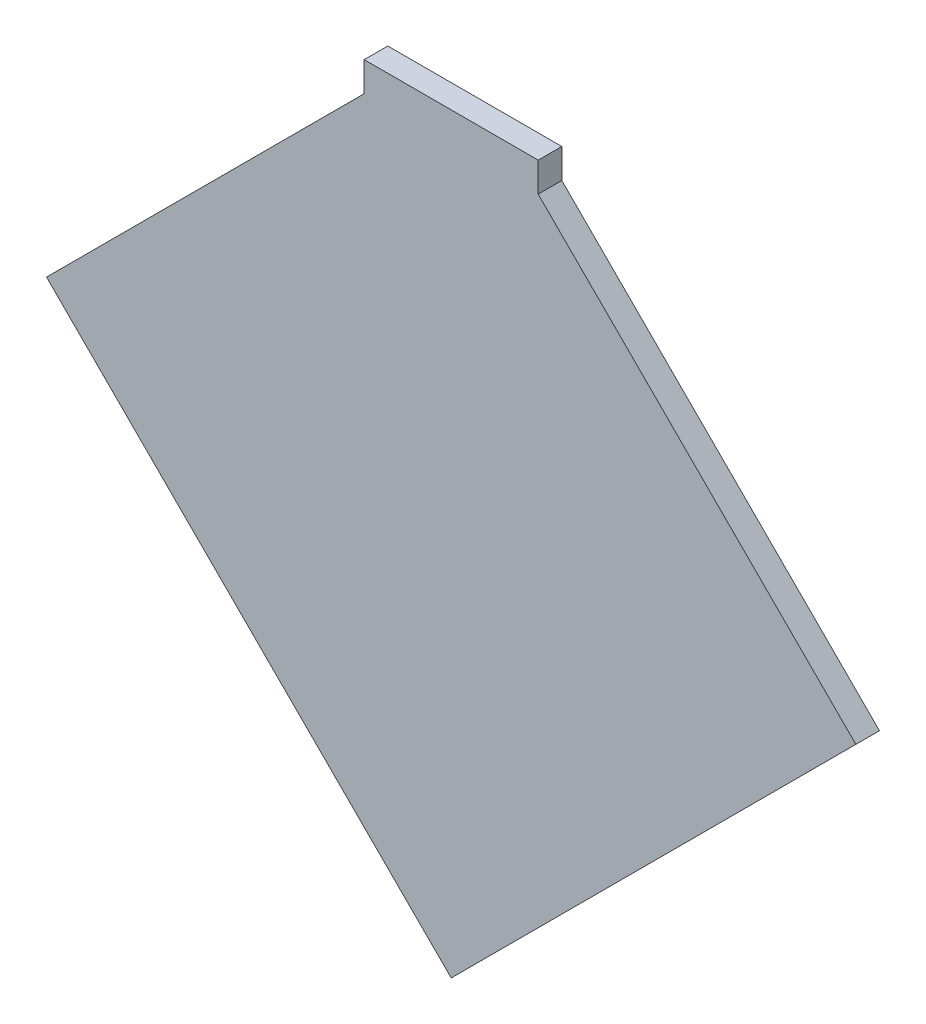
SolidWorks part; units mm, degrees
ref_plane "Front Plane" through (0, 0, 0) normal (0, 0, 1) x (1, 0, 0)
ref_plane "Top Plane" through (0, 0, 0) normal (0, 1, 0) x (1, 0, 0)
ref_plane "Right Plane" through (0, 0, 0) normal (1, 0, 0) x (0, 0, -1)
sketch "Sketch1" plane through (0, 0, 0) normal (0, 0, 1) x (1, 0, 0)
  line L0 (-4.6243, 15.9525) -> (-20.5768, 0)
  line L1 (-20.5768, 0) -> (0, -20.5768)
  line L2 (0, -20.5768) -> (20.5768, 0)
  line L3 (20.5768, 0) -> (4.6243, 15.9525)
  line L4 (4.6243, 15.9525) -> (4.4828, 15.9525)
  line L5 (4.4828, 15.9525) -> (20.4354, 0)
  line L6 (20.4354, 0) -> (0, -20.4354)
  line L7 (0, -20.4354) -> (-20.4354, 0)
  line L8 (-20.4354, 0) -> (-4.4828, 15.9525)
  line L9 (-4.4828, 15.9525) -> (-4.6243, 15.9525)
  line L20 (0, -20.8597) -> (20.8597, 0)
  line L21 (20.8597, 0) -> (4.7071, 16.1525)
  line L22 (4.7071, 16.1525) -> (4, 16.1525)
  line L23 (4, 16.1525) -> (20.1525, 0)
  line L24 (20.1525, 0) -> (0, -20.1525)
  line L25 (0, -20.1525) -> (-20.1525, 0)
  line L26 (-20.1525, 0) -> (-4, 16.1525)
  line L27 (-4, 16.1525) -> (-4.7071, 16.1525)
  line L28 (-4.7071, 16.1525) -> (-20.8597, 0)
  line L29 (-20.8597, 0) -> (0, -20.8597)
  line L30 (-4.6243, 15.9525) -> (-4.4243, 16.1525)
  line L31 (4.6243, 15.9525) -> (4.4243, 16.1525)
  line L32 (-4.4243, 16.1525) -> (4.4243, 16.1525)
  dimension "D2" = 0.2
extrude "Boss-Extrude1" add sketch "Sketch1" along normal blind 1.2 contours L32 L26 L25 L24 L23 | L4 L31 L22 L23 L24 L25 L26 L27 L30 L9 L8 L7 L6 L5 | L8 L9 L0 L1 L2 L3 L4 L5 L6 L7
sketch "Sketch2" plane through (0, 0, 0) normal (0, 0, 1) x (1, 0, 0)
  line L1 (-4.4243, 16.1525) -> (4.4243, 16.1525)
  line L2 (-4.4243, 16.1525) -> (-4.4243, 17.6525)
  line L3 (-4.4243, 17.6525) -> (4.4243, 17.6525)
  line L4 (4.4243, 16.1525) -> (4.4243, 17.6525)
  dimension "D1" = 1.5
extrude "Boss-Extrude2" add sketch "Sketch2" along normal up to surface (1.2 mm away) up to face at (0, 2.3457, 1.2)
